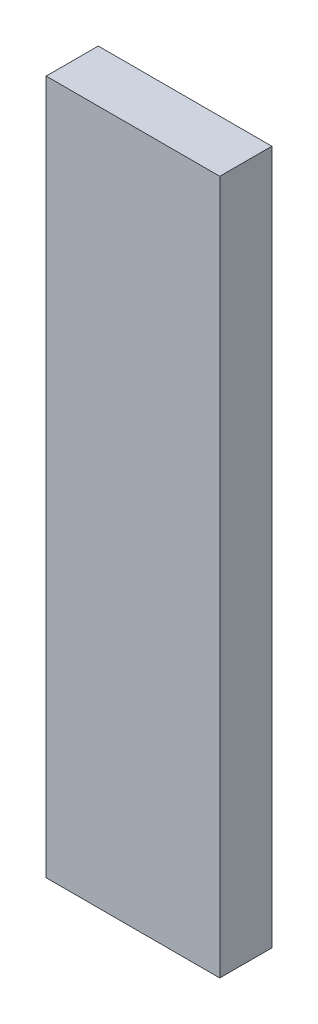
SolidWorks part; units mm, degrees
material "Acrylic (Medium-high impact)"
ref_plane "Front Plane" through (0, 0, 0) normal (0, 0, 1) x (1, 0, 0)
ref_plane "Top Plane" through (0, 0, 0) normal (0, 1, 0) x (1, 0, 0)
ref_plane "Right Plane" through (0, 0, 0) normal (1, 0, 0) x (0, 0, -1)
sketch "Sketch1" plane through (0, 0, 0) normal (0, 0, 1) x (1, 0, 0)
  line L0 (7.5, 0) -> (-7.5, 0)
  line L1 (55, 0) -> (-55, 0) construction
  line L2 (-7.5, 0) -> (-7.5, 60)
  line L3 (-7.5, 60) -> (0, 60)
  line L6 (0, -55) -> (0, 55) construction
  line L8 (7.5, 60) -> (0, 60)
  line L9 (7.5, 0) -> (7.5, 60)
  point P12 (0, 66)
  point P15 (0, 0)
  dimension "D1" = 7.5
  dimension "D4" = 60
extrude "Boss-Extrude1" add sketch "Sketch1" along normal blind 4.5
